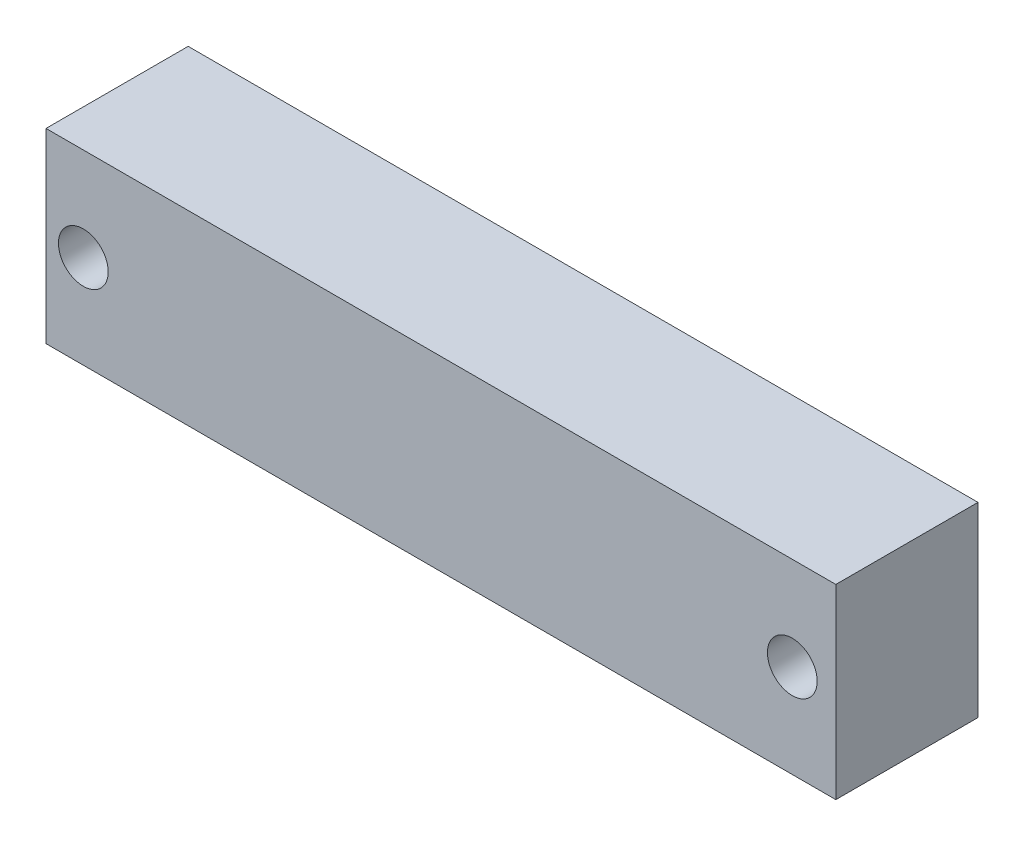
SolidWorks part; units mm, degrees
ref_plane "Front Plane" through (0, 0, 0) normal (0, 0, 1) x (1, 0, 0)
ref_plane "Top Plane" through (0, 0, 0) normal (0, 1, 0) x (1, 0, 0)
ref_plane "Right Plane" through (0, 0, 0) normal (1, 0, 0) x (0, 0, -1)
sketch "Sketch1" plane through (0, 0, 0) normal (0, 0, 1) x (1, 0, 0)
  line L1 (-83.9447, -6.3134) -> (-20.4447, -6.3134)
  line L2 (-83.9447, -6.3134) -> (-83.9447, -21.2994)
  line L3 (-83.9447, -21.2994) -> (-20.4447, -21.2994)
  line L4 (-20.4447, -6.3134) -> (-20.4447, -21.2994)
  dimension "D1" = 63.5
  dimension "D2" = 14.986
extrude "Boss-Extrude1" add sketch "Sketch1" along normal blind 11.43 contours L2 L1 L4 L3
sketch "Sketch2" plane through (0, 0, 11.43) normal (0, 0, 1) x (1, 0, 0)
  circle A0 centre (-80.9447, -13.8064) radius 2
  circle A1 centre (-23.9447, -13.8064) radius 2
  point P12 (0, 0)
  point P13 (-20.4447, -13.8064)
extrude "Cut-Extrude3" cut sketch "Sketch2" against normal blind 20 contours A0 | A1
